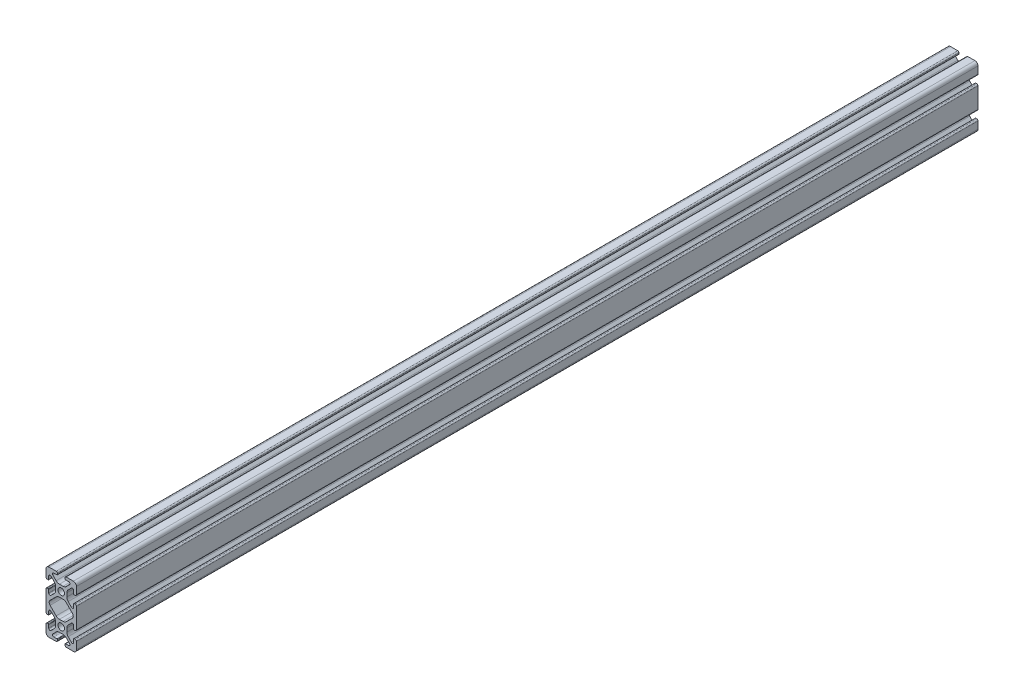
SolidWorks part; units mm, degrees
ref_plane "Front Plane" through (0, 0, 0) normal (0, 0, 1) x (1, 0, 0)
ref_plane "Top Plane" through (0, 0, 0) normal (0, 1, 0) x (1, 0, 0)
ref_plane "Right Plane" through (0, 0, 0) normal (1, 0, 0) x (0, 0, -1)
sketch "Sketch1" plane through (0, 0, 0) normal (0, 0, 1) x (1, 0, 0)
  line L0 (0, 10) -> (0, 20) construction
  line L1 (0, 10) -> (10, 10) construction
  line L2 (0, 10) -> (-10, 20) construction
  line L3 (-8, 20) -> (-3.3, 20)
  line L4 (-10, 20) -> (0, 20) construction
  line L6 (-2.8, 18.2) -> (-4.9051, 18.2)
  line L10 (0, 13.7) -> (-1.2022, 13.7)
  line L11 (-3.3236, 14.5787) -> (-5.5025, 16.7576)
  line L24 (0, 10) -> (-10, 10) construction
  line L25 (-10, 10) -> (0, 10) construction
  line L27 (-10, 0) -> (-10, 20) construction
  line L28 (0, 20) -> (10, 20) construction
  line L29 (-2.5, 18.5) -> (-2.5, 19.2)
  line L30 (-10, -20) -> (10, -20) construction
  line L31 (0, 20) -> (0, -20) construction
  arc A0 (-9.4142, 19.4142) -> (-8, 20) centre (-8, 18) cw
  arc A5 (-3.3, 20) -> (-2.5, 19.2) centre (-3.3, 19.2) cw
  arc A6 (-1.2022, 13.7) -> (-3.3236, 14.5787) centre (-1.2022, 16.7) cw
  circle A16 centre (0, 10) radius 2.15
  arc A18 (-5.5025, 16.7576) -> (-4.9051, 18.2) centre (-4.9051, 17.3551) cw
  arc A20 (-2.8, 18.2) -> (-2.5, 18.5) centre (-2.8, 18.5) ccw
  point P15 (0, -20)
  point P24 (0, 0)
  point P42 (-2.4449, 13.7)
  point P80 (-10, 10)
  dimension "D11" = 2
  dimension "D15" = 3
  dimension "Center Hole Diameter" = 4.3
  dimension "D7" = 0.8
  dimension "D8" = 0.3
  dimension "D4" = 0.8449
  dimension "D1" = 45
  dimension "Rail Width" = 20
  dimension "T-Slot Depth" = 6.3
  dimension "D9" = 1.8
  dimension "D23" = 7.4
  dimension "D5" = 11.5
  dimension "T-Slot Width" = 5
  dimension "D3" = 1.775
  dimension "D6" = 9.8102
  dimension "Rail Height" = 40
sketch "Sketch2" plane through (0, 0, 0) normal (1, 0, 0) x (0, 0, -1)
  line L0 (-304.8, 0) -> (304.8, 0)
  line L1 (-304.8, -20) -> (-304.8, 20)
  line L2 (0, 10) -> (0, 20) construction
  line L3 (0, 0) -> (0, 20) construction
  line L4 (304.8, -20) -> (304.8, 20)
  line L5 (-10, 10) -> (10, 10) construction
  point P0 (-279.8, 0)
  point P3 (0, 0)
  point P7 (279.8, 0)
  point P11 (-304.8, 0)
  point P14 (304.8, 0)
  point P23 (0, 10)
  dimension "D1" = 25
  dimension "Length" = 609.6
sketch "Sketch3" plane through (0, 0, 0) normal (0, 0, 1) x (1, 0, 0)
  line L0 (-2.5, 18.5) -> (-2.5, 19.2) construction
  line L1 (0, 10) -> (-10, 20) construction
  line L2 (0, 10) -> (-10, 20) construction
  line L5 (-8, 20) -> (-3.3, 20) construction
  line L6 (-2.8, 18.2) -> (-4.9051, 18.2) construction
  line L7 (-8.5, 7.5) -> (-9.2, 7.5)
  line L17 (-2.5, 18.5) -> (-2.5, 19.2)
  line L19 (-2.8, 18.2) -> (-4.9051, 18.2)
  line L21 (-3.7, 10) -> (0, 10) construction
  line L22 (-3.7, 8.7978) -> (-3.7, 11.2022)
  line L23 (-4.5787, 13.3236) -> (-6.7576, 15.5025)
  line L42 (-3.3236, 14.5787) -> (-5.5025, 16.7576) construction
  line L43 (0, 13.7) -> (-1.2022, 13.7) construction
  line L44 (-8, 20) -> (-3.3, 20)
  line L47 (-3.3236, 14.5787) -> (-5.5025, 16.7576)
  line L48 (1.2022, 13.7) -> (-1.2022, 13.7)
  line L59 (0, 13.7) -> (0, 12.15) construction
  line L60 (-10, 18) -> (-10, 13.3)
  line L61 (-8.2, 12.8) -> (-8.2, 14.9051)
  line L62 (-8.5, 12.5) -> (-9.2, 12.5)
  line L63 (-8.2, 7.2) -> (-8.2, 5.0949)
  line L64 (-10, 0) -> (-10, 6.7)
  line L65 (1.2022, 6.3) -> (-1.2022, 6.3)
  line L66 (-3.3236, 5.4213) -> (-7.3307, 1.4142)
  line L68 (-4.5787, 6.6764) -> (-6.7576, 4.4975)
  line L73 (10, 0) -> (-10, 0) construction
  line L78 (4.5787, 6.6764) -> (6.7576, 4.4975)
  line L79 (3.3236, 5.4213) -> (7.3307, 1.4142)
  line L81 (10, 0) -> (10, 6.7)
  line L82 (8.2, 7.2) -> (8.2, 5.0949)
  line L83 (8.5, 12.5) -> (9.2, 12.5)
  line L84 (8.2, 12.8) -> (8.2, 14.9051)
  line L85 (10, 18) -> (10, 13.3)
  line L87 (3.3236, 14.5787) -> (5.5025, 16.7576)
  line L88 (8, 20) -> (3.3, 20)
  line L89 (4.5787, 13.3236) -> (6.7576, 15.5025)
  line L90 (3.7, 8.7978) -> (3.7, 11.2022)
  line L91 (2.8, 18.2) -> (4.9051, 18.2)
  line L92 (2.5, 18.5) -> (2.5, 19.2)
  line L93 (8.5, 7.5) -> (9.2, 7.5)
  line L94 (-10, 0) -> (-7.9165, 0)
  line L96 (7.9165, 0) -> (10, 0)
  arc A0 (-8, 20) -> (-9.4142, 19.4142) centre (-8, 18) ccw construction
  arc A1 (-2.8, 18.2) -> (-2.5, 18.5) centre (-2.8, 18.5) ccw construction
  arc A3 (-2.8, 18.2) -> (-2.5, 18.5) centre (-2.8, 18.5) ccw
  arc A5 (-8, 20) -> (-10, 18) centre (-8, 18) ccw
  arc A10 (-3.3236, 5.4213) -> (-1.2022, 6.3) centre (-1.2022, 3.3) cw
  circle A13 centre (0, 10) radius 2.15 construction
  circle A14 centre (0, 10) radius 2.15
  arc A15 (-4.5787, 13.3236) -> (-3.7, 11.2022) centre (-6.7, 11.2022) cw
  arc A16 (-8.2, 14.9051) -> (-6.7576, 15.5025) centre (-7.3551, 14.9051) cw
  arc A17 (-9.2, 12.5) -> (-10, 13.3) centre (-9.2, 13.3) cw
  arc A18 (-8.2, 12.8) -> (-8.5, 12.5) centre (-8.5, 12.8) cw
  arc A36 (-2.5, 19.2) -> (-3.3, 20) centre (-3.3, 19.2) ccw construction
  arc A38 (-4.9051, 18.2) -> (-5.5025, 16.7576) centre (-4.9051, 17.3551) ccw construction
  arc A39 (-3.3236, 14.5787) -> (-1.2022, 13.7) centre (-1.2022, 16.7) ccw construction
  arc A41 (-2.5, 19.2) -> (-3.3, 20) centre (-3.3, 19.2) ccw
  arc A43 (-4.9051, 18.2) -> (-5.5025, 16.7576) centre (-4.9051, 17.3551) ccw
  arc A44 (-3.3236, 14.5787) -> (-1.2022, 13.7) centre (-1.2022, 16.7) ccw
  arc A47 (-8.2, 7.2) -> (-8.5, 7.5) centre (-8.5, 7.2) ccw
  arc A48 (-9.2, 7.5) -> (-10, 6.7) centre (-9.2, 6.7) ccw
  arc A49 (-8.2, 5.0949) -> (-6.7576, 4.4975) centre (-7.3551, 5.0949) ccw
  arc A50 (-4.5787, 6.6764) -> (-3.7, 8.7978) centre (-6.7, 8.7978) ccw
  arc A54 (-7.9165, 0) -> (-7.3307, 1.4142) centre (-5.9165, 0) cw
  arc A57 (7.9165, 0) -> (7.3307, 1.4142) centre (5.9165, 0) ccw
  arc A58 (4.5787, 6.6764) -> (3.7, 8.7978) centre (6.7, 8.7978) cw
  arc A59 (8.2, 5.0949) -> (6.7576, 4.4975) centre (7.3551, 5.0949) cw
  arc A60 (9.2, 7.5) -> (10, 6.7) centre (9.2, 6.7) cw
  arc A61 (8.2, 7.2) -> (8.5, 7.5) centre (8.5, 7.2) cw
  arc A62 (3.3236, 14.5787) -> (1.2022, 13.7) centre (1.2022, 16.7) cw
  arc A63 (4.9051, 18.2) -> (5.5025, 16.7576) centre (4.9051, 17.3551) cw
  arc A64 (2.5, 19.2) -> (3.3, 20) centre (3.3, 19.2) cw
  arc A65 (8.2, 12.8) -> (8.5, 12.5) centre (8.5, 12.8) ccw
  arc A66 (9.2, 12.5) -> (10, 13.3) centre (9.2, 13.3) ccw
  arc A67 (8.2, 14.9051) -> (6.7576, 15.5025) centre (7.3551, 14.9051) ccw
  arc A68 (4.5787, 13.3236) -> (3.7, 11.2022) centre (6.7, 11.2022) ccw
  arc A70 (3.3236, 5.4213) -> (1.2022, 6.3) centre (1.2022, 3.3) ccw
  arc A71 (8, 20) -> (10, 18) centre (8, 18) cw
  arc A72 (2.8, 18.2) -> (2.5, 18.5) centre (2.8, 18.5) cw
  point P59 (-10, 2)
  point P71 (0, 0)
  point P116 (0, 6.3)
extrude "Boss-Extrude1" add sketch "Sketch3" along normal mid plane 609.6
pattern_circular "CirPattern1" count 2 over 360 about axis through (0, 0, 0) along (0, 0, 1) of "Boss-Extrude1"
sketch "Sketch4" plane through (0, 0, 304.8) normal (0, 0, 1) x (1, 0, 0)
  line L0 (7.3307, -1.4142) -> (3.3236, -5.4213) construction
  line L1 (-3.3236, -5.4213) -> (-7.3307, -1.4142) construction
  line L2 (1.2022, -6.3) -> (-1.2022, -6.3) construction
  line L3 (3.3236, 5.4213) -> (7.3307, 1.4142) construction
  line L4 (-1.2022, 6.3) -> (1.2022, 6.3) construction
  line L5 (-7.3307, 1.4142) -> (-3.3236, 5.4213) construction
  line L6 (7.3307, -1.4142) -> (3.3236, -5.4213)
  line L7 (-3.3236, -5.4213) -> (-7.3307, -1.4142)
  line L8 (1.2022, -6.3) -> (-1.2022, -6.3)
  line L9 (3.3236, 5.4213) -> (7.3307, 1.4142)
  line L10 (-1.2022, 6.3) -> (1.2022, 6.3)
  line L11 (-7.3307, 1.4142) -> (-3.3236, 5.4213)
  line L52 (-2.5, 18.5) -> (-2.5, 19.2)
  line L53 (-3.3, 20) -> (-8, 20)
  line L54 (-10, 18) -> (-10, 13.3)
  line L55 (-9.2, 12.5) -> (-8.5, 12.5)
  line L56 (-8.2, 12.8) -> (-8.2, 14.9051)
  line L57 (-6.7576, 15.5025) -> (-4.5787, 13.3236)
  line L58 (-3.7, 11.2022) -> (-3.7, 8.7978)
  line L59 (-4.5787, 6.6764) -> (-6.7576, 4.4975)
  line L60 (-8.2, 5.0949) -> (-8.2, 7.2)
  line L61 (-8.5, 7.5) -> (-9.2, 7.5)
  line L62 (-10, 6.7) -> (-10, -6.7)
  line L63 (-9.2, -7.5) -> (-8.5, -7.5)
  line L64 (-8.2, -7.2) -> (-8.2, -5.0949)
  line L65 (-6.7576, -4.4975) -> (-4.5787, -6.6764)
  line L66 (-3.7, -8.7978) -> (-3.7, -11.2022)
  line L67 (-4.5787, -13.3236) -> (-6.7576, -15.5025)
  line L68 (-8.2, -14.9051) -> (-8.2, -12.8)
  line L69 (-8.5, -12.5) -> (-9.2, -12.5)
  line L70 (-10, -13.3) -> (-10, -18)
  line L71 (-8, -20) -> (-3.3, -20)
  line L72 (-2.5, -19.2) -> (-2.5, -18.5)
  line L73 (-2.8, -18.2) -> (-4.9051, -18.2)
  line L74 (-5.5025, -16.7576) -> (-3.3236, -14.5787)
  line L75 (-1.2022, -13.7) -> (1.2022, -13.7)
  line L76 (3.3236, -14.5787) -> (5.5025, -16.7576)
  line L77 (4.9051, -18.2) -> (2.8, -18.2)
  line L78 (2.5, -18.5) -> (2.5, -19.2)
  line L79 (3.3, -20) -> (8, -20)
  line L80 (10, -18) -> (10, -13.3)
  line L81 (9.2, -12.5) -> (8.5, -12.5)
  line L82 (8.2, -12.8) -> (8.2, -14.9051)
  line L83 (6.7576, -15.5025) -> (4.5787, -13.3236)
  line L84 (3.7, -11.2022) -> (3.7, -8.7978)
  line L85 (4.5787, -6.6764) -> (6.7576, -4.4975)
  line L86 (8.2, -5.0949) -> (8.2, -7.2)
  line L87 (8.5, -7.5) -> (9.2, -7.5)
  line L88 (10, -6.7) -> (10, 6.7)
  line L89 (9.2, 7.5) -> (8.5, 7.5)
  line L90 (8.2, 7.2) -> (8.2, 5.0949)
  line L91 (6.7576, 4.4975) -> (4.5787, 6.6764)
  line L92 (3.7, 8.7978) -> (3.7, 11.2022)
  line L93 (4.5787, 13.3236) -> (6.7576, 15.5025)
  line L94 (8.2, 14.9051) -> (8.2, 12.8)
  line L95 (8.5, 12.5) -> (9.2, 12.5)
  line L96 (10, 13.3) -> (10, 18)
  line L97 (8, 20) -> (3.3, 20)
  line L98 (2.5, 19.2) -> (2.5, 18.5)
  line L99 (2.8, 18.2) -> (4.9051, 18.2)
  line L100 (5.5025, 16.7576) -> (3.3236, 14.5787)
  line L101 (1.2022, 13.7) -> (-1.2022, 13.7)
  line L102 (-3.3236, 14.5787) -> (-5.5025, 16.7576)
  line L103 (-4.9051, 18.2) -> (-2.8, 18.2)
  line L104 (-2.5, 18.5) -> (-2.5, 19.2)
  line L105 (-3.3, 20) -> (-8, 20)
  line L106 (-10, 18) -> (-10, 13.3)
  line L107 (-9.2, 12.5) -> (-8.5, 12.5)
  line L108 (-8.2, 12.8) -> (-8.2, 14.9051)
  line L109 (-6.7576, 15.5025) -> (-4.5787, 13.3236)
  line L110 (-3.7, 11.2022) -> (-3.7, 8.7978)
  line L111 (-4.5787, 6.6764) -> (-6.7576, 4.4975)
  line L112 (-8.2, 5.0949) -> (-8.2, 7.2)
  line L113 (-8.5, 7.5) -> (-9.2, 7.5)
  line L114 (-10, 6.7) -> (-10, -6.7)
  line L115 (-9.2, -7.5) -> (-8.5, -7.5)
  line L116 (-8.2, -7.2) -> (-8.2, -5.0949)
  line L117 (-6.7576, -4.4975) -> (-4.5787, -6.6764)
  line L118 (-3.7, -8.7978) -> (-3.7, -11.2022)
  line L119 (-4.5787, -13.3236) -> (-6.7576, -15.5025)
  line L120 (-8.2, -14.9051) -> (-8.2, -12.8)
  line L121 (-8.5, -12.5) -> (-9.2, -12.5)
  line L122 (-10, -13.3) -> (-10, -18)
  line L123 (-8, -20) -> (-3.3, -20)
  line L124 (-2.5, -19.2) -> (-2.5, -18.5)
  line L125 (-2.8, -18.2) -> (-4.9051, -18.2)
  line L126 (-5.5025, -16.7576) -> (-3.3236, -14.5787)
  line L127 (-1.2022, -13.7) -> (1.2022, -13.7)
  line L128 (3.3236, -14.5787) -> (5.5025, -16.7576)
  line L129 (4.9051, -18.2) -> (2.8, -18.2)
  line L130 (2.5, -18.5) -> (2.5, -19.2)
  line L131 (3.3, -20) -> (8, -20)
  line L132 (10, -18) -> (10, -13.3)
  line L133 (9.2, -12.5) -> (8.5, -12.5)
  line L134 (8.2, -12.8) -> (8.2, -14.9051)
  line L135 (6.7576, -15.5025) -> (4.5787, -13.3236)
  line L136 (3.7, -11.2022) -> (3.7, -8.7978)
  line L137 (4.5787, -6.6764) -> (6.7576, -4.4975)
  line L138 (8.2, -5.0949) -> (8.2, -7.2)
  line L139 (8.5, -7.5) -> (9.2, -7.5)
  line L140 (10, -6.7) -> (10, 6.7)
  line L141 (9.2, 7.5) -> (8.5, 7.5)
  line L142 (8.2, 7.2) -> (8.2, 5.0949)
  line L143 (6.7576, 4.4975) -> (4.5787, 6.6764)
  line L144 (3.7, 8.7978) -> (3.7, 11.2022)
  line L145 (4.5787, 13.3236) -> (6.7576, 15.5025)
  line L146 (8.2, 14.9051) -> (8.2, 12.8)
  line L147 (8.5, 12.5) -> (9.2, 12.5)
  line L148 (10, 13.3) -> (10, 18)
  line L149 (8, 20) -> (3.3, 20)
  line L150 (2.5, 19.2) -> (2.5, 18.5)
  line L151 (2.8, 18.2) -> (4.9051, 18.2)
  line L152 (5.5025, 16.7576) -> (3.3236, 14.5787)
  line L153 (1.2022, 13.7) -> (-1.2022, 13.7)
  line L154 (-3.3236, 14.5787) -> (-5.5025, 16.7576)
  line L155 (-4.9051, 18.2) -> (-2.8, 18.2)
  circle A0 centre (0, 10) radius 2.15 construction
  arc A1 (-7.3307, 1.4142) -> (-7.3307, -1.4142) centre (-5.9165, 0) ccw construction
  arc A2 (-3.3236, -5.4213) -> (-1.2022, -6.3) centre (-1.2022, -3.3) ccw construction
  arc A3 (1.2022, -6.3) -> (3.3236, -5.4213) centre (1.2022, -3.3) ccw construction
  circle A4 centre (0, -10) radius 2.15 construction
  arc A5 (7.3307, -1.4142) -> (7.3307, 1.4142) centre (5.9165, 0) ccw construction
  arc A6 (3.3236, 5.4213) -> (1.2022, 6.3) centre (1.2022, 3.3) ccw construction
  arc A7 (-1.2022, 6.3) -> (-3.3236, 5.4213) centre (-1.2022, 3.3) ccw construction
  circle A8 centre (0, 10) radius 2.15
  arc A9 (-7.3307, 1.4142) -> (-7.3307, -1.4142) centre (-5.9165, 0) ccw
  arc A10 (-3.3236, -5.4213) -> (-1.2022, -6.3) centre (-1.2022, -3.3) ccw
  arc A11 (1.2022, -6.3) -> (3.3236, -5.4213) centre (1.2022, -3.3) ccw
  circle A12 centre (0, -10) radius 2.15
  arc A13 (7.3307, -1.4142) -> (7.3307, 1.4142) centre (5.9165, 0) ccw
  arc A14 (3.3236, 5.4213) -> (1.2022, 6.3) centre (1.2022, 3.3) ccw
  arc A15 (-1.2022, 6.3) -> (-3.3236, 5.4213) centre (-1.2022, 3.3) ccw
  arc A52 (-2.8, 18.2) -> (-2.5, 18.5) centre (-2.8, 18.5) ccw
  arc A53 (-2.5, 19.2) -> (-3.3, 20) centre (-3.3, 19.2) ccw
  arc A54 (-8, 20) -> (-10, 18) centre (-8, 18) ccw
  arc A55 (-10, 13.3) -> (-9.2, 12.5) centre (-9.2, 13.3) ccw
  arc A56 (-8.5, 12.5) -> (-8.2, 12.8) centre (-8.5, 12.8) ccw
  arc A57 (-6.7576, 15.5025) -> (-8.2, 14.9051) centre (-7.3551, 14.9051) ccw
  arc A58 (-3.7, 11.2022) -> (-4.5787, 13.3236) centre (-6.7, 11.2022) ccw
  arc A59 (-4.5787, 6.6764) -> (-3.7, 8.7978) centre (-6.7, 8.7978) ccw
  arc A60 (-8.2, 5.0949) -> (-6.7576, 4.4975) centre (-7.3551, 5.0949) ccw
  arc A61 (-8.2, 7.2) -> (-8.5, 7.5) centre (-8.5, 7.2) ccw
  arc A62 (-9.2, 7.5) -> (-10, 6.7) centre (-9.2, 6.7) ccw
  arc A63 (-10, -6.7) -> (-9.2, -7.5) centre (-9.2, -6.7) ccw
  arc A64 (-8.5, -7.5) -> (-8.2, -7.2) centre (-8.5, -7.2) ccw
  arc A65 (-6.7576, -4.4975) -> (-8.2, -5.0949) centre (-7.3551, -5.0949) ccw
  arc A66 (-3.7, -8.7978) -> (-4.5787, -6.6764) centre (-6.7, -8.7978) ccw
  arc A67 (-4.5787, -13.3236) -> (-3.7, -11.2022) centre (-6.7, -11.2022) ccw
  arc A68 (-8.2, -14.9051) -> (-6.7576, -15.5025) centre (-7.3551, -14.9051) ccw
  arc A69 (-8.2, -12.8) -> (-8.5, -12.5) centre (-8.5, -12.8) ccw
  arc A70 (-9.2, -12.5) -> (-10, -13.3) centre (-9.2, -13.3) ccw
  arc A71 (-10, -18) -> (-8, -20) centre (-8, -18) ccw
  arc A72 (-3.3, -20) -> (-2.5, -19.2) centre (-3.3, -19.2) ccw
  arc A73 (-2.5, -18.5) -> (-2.8, -18.2) centre (-2.8, -18.5) ccw
  arc A74 (-5.5025, -16.7576) -> (-4.9051, -18.2) centre (-4.9051, -17.3551) ccw
  arc A75 (-1.2022, -13.7) -> (-3.3236, -14.5787) centre (-1.2022, -16.7) ccw
  arc A76 (3.3236, -14.5787) -> (1.2022, -13.7) centre (1.2022, -16.7) ccw
  arc A77 (4.9051, -18.2) -> (5.5025, -16.7576) centre (4.9051, -17.3551) ccw
  arc A78 (2.8, -18.2) -> (2.5, -18.5) centre (2.8, -18.5) ccw
  arc A79 (2.5, -19.2) -> (3.3, -20) centre (3.3, -19.2) ccw
  arc A80 (8, -20) -> (10, -18) centre (8, -18) ccw
  arc A81 (10, -13.3) -> (9.2, -12.5) centre (9.2, -13.3) ccw
  arc A82 (8.5, -12.5) -> (8.2, -12.8) centre (8.5, -12.8) ccw
  arc A83 (6.7576, -15.5025) -> (8.2, -14.9051) centre (7.3551, -14.9051) ccw
  arc A84 (3.7, -11.2022) -> (4.5787, -13.3236) centre (6.7, -11.2022) ccw
  arc A85 (4.5787, -6.6764) -> (3.7, -8.7978) centre (6.7, -8.7978) ccw
  arc A86 (8.2, -5.0949) -> (6.7576, -4.4975) centre (7.3551, -5.0949) ccw
  arc A87 (8.2, -7.2) -> (8.5, -7.5) centre (8.5, -7.2) ccw
  arc A88 (9.2, -7.5) -> (10, -6.7) centre (9.2, -6.7) ccw
  arc A89 (10, 6.7) -> (9.2, 7.5) centre (9.2, 6.7) ccw
  arc A90 (8.5, 7.5) -> (8.2, 7.2) centre (8.5, 7.2) ccw
  arc A91 (6.7576, 4.4975) -> (8.2, 5.0949) centre (7.3551, 5.0949) ccw
  arc A92 (3.7, 8.7978) -> (4.5787, 6.6764) centre (6.7, 8.7978) ccw
  arc A93 (4.5787, 13.3236) -> (3.7, 11.2022) centre (6.7, 11.2022) ccw
  arc A94 (8.2, 14.9051) -> (6.7576, 15.5025) centre (7.3551, 14.9051) ccw
  arc A95 (8.2, 12.8) -> (8.5, 12.5) centre (8.5, 12.8) ccw
  arc A96 (9.2, 12.5) -> (10, 13.3) centre (9.2, 13.3) ccw
  arc A97 (10, 18) -> (8, 20) centre (8, 18) ccw
  arc A98 (3.3, 20) -> (2.5, 19.2) centre (3.3, 19.2) ccw
  arc A99 (2.5, 18.5) -> (2.8, 18.2) centre (2.8, 18.5) ccw
  arc A100 (5.5025, 16.7576) -> (4.9051, 18.2) centre (4.9051, 17.3551) ccw
  arc A101 (1.2022, 13.7) -> (3.3236, 14.5787) centre (1.2022, 16.7) ccw
  arc A102 (-3.3236, 14.5787) -> (-1.2022, 13.7) centre (-1.2022, 16.7) ccw
  arc A103 (-4.9051, 18.2) -> (-5.5025, 16.7576) centre (-4.9051, 17.3551) ccw
  arc A104 (-2.8, 18.2) -> (-2.5, 18.5) centre (-2.8, 18.5) ccw
  arc A105 (-2.5, 19.2) -> (-3.3, 20) centre (-3.3, 19.2) ccw
  arc A106 (-8, 20) -> (-10, 18) centre (-8, 18) ccw
  arc A107 (-10, 13.3) -> (-9.2, 12.5) centre (-9.2, 13.3) ccw
  arc A108 (-8.5, 12.5) -> (-8.2, 12.8) centre (-8.5, 12.8) ccw
  arc A109 (-6.7576, 15.5025) -> (-8.2, 14.9051) centre (-7.3551, 14.9051) ccw
  arc A110 (-3.7, 11.2022) -> (-4.5787, 13.3236) centre (-6.7, 11.2022) ccw
  arc A111 (-4.5787, 6.6764) -> (-3.7, 8.7978) centre (-6.7, 8.7978) ccw
  arc A112 (-8.2, 5.0949) -> (-6.7576, 4.4975) centre (-7.3551, 5.0949) ccw
  arc A113 (-8.2, 7.2) -> (-8.5, 7.5) centre (-8.5, 7.2) ccw
  arc A114 (-9.2, 7.5) -> (-10, 6.7) centre (-9.2, 6.7) ccw
  arc A115 (-10, -6.7) -> (-9.2, -7.5) centre (-9.2, -6.7) ccw
  arc A116 (-8.5, -7.5) -> (-8.2, -7.2) centre (-8.5, -7.2) ccw
  arc A117 (-6.7576, -4.4975) -> (-8.2, -5.0949) centre (-7.3551, -5.0949) ccw
  arc A118 (-3.7, -8.7978) -> (-4.5787, -6.6764) centre (-6.7, -8.7978) ccw
  arc A119 (-4.5787, -13.3236) -> (-3.7, -11.2022) centre (-6.7, -11.2022) ccw
  arc A120 (-8.2, -14.9051) -> (-6.7576, -15.5025) centre (-7.3551, -14.9051) ccw
  arc A121 (-8.2, -12.8) -> (-8.5, -12.5) centre (-8.5, -12.8) ccw
  arc A122 (-9.2, -12.5) -> (-10, -13.3) centre (-9.2, -13.3) ccw
  arc A123 (-10, -18) -> (-8, -20) centre (-8, -18) ccw
  arc A124 (-3.3, -20) -> (-2.5, -19.2) centre (-3.3, -19.2) ccw
  arc A125 (-2.5, -18.5) -> (-2.8, -18.2) centre (-2.8, -18.5) ccw
  arc A126 (-5.5025, -16.7576) -> (-4.9051, -18.2) centre (-4.9051, -17.3551) ccw
  arc A127 (-1.2022, -13.7) -> (-3.3236, -14.5787) centre (-1.2022, -16.7) ccw
  arc A128 (3.3236, -14.5787) -> (1.2022, -13.7) centre (1.2022, -16.7) ccw
  arc A129 (4.9051, -18.2) -> (5.5025, -16.7576) centre (4.9051, -17.3551) ccw
  arc A130 (2.8, -18.2) -> (2.5, -18.5) centre (2.8, -18.5) ccw
  arc A131 (2.5, -19.2) -> (3.3, -20) centre (3.3, -19.2) ccw
  arc A132 (8, -20) -> (10, -18) centre (8, -18) ccw
  arc A133 (10, -13.3) -> (9.2, -12.5) centre (9.2, -13.3) ccw
  arc A134 (8.5, -12.5) -> (8.2, -12.8) centre (8.5, -12.8) ccw
  arc A135 (6.7576, -15.5025) -> (8.2, -14.9051) centre (7.3551, -14.9051) ccw
  arc A136 (3.7, -11.2022) -> (4.5787, -13.3236) centre (6.7, -11.2022) ccw
  arc A137 (4.5787, -6.6764) -> (3.7, -8.7978) centre (6.7, -8.7978) ccw
  arc A138 (8.2, -5.0949) -> (6.7576, -4.4975) centre (7.3551, -5.0949) ccw
  arc A139 (8.2, -7.2) -> (8.5, -7.5) centre (8.5, -7.2) ccw
  arc A140 (9.2, -7.5) -> (10, -6.7) centre (9.2, -6.7) ccw
  arc A141 (10, 6.7) -> (9.2, 7.5) centre (9.2, 6.7) ccw
  arc A142 (8.5, 7.5) -> (8.2, 7.2) centre (8.5, 7.2) ccw
  arc A143 (6.7576, 4.4975) -> (8.2, 5.0949) centre (7.3551, 5.0949) ccw
  arc A144 (3.7, 8.7978) -> (4.5787, 6.6764) centre (6.7, 8.7978) ccw
  arc A145 (4.5787, 13.3236) -> (3.7, 11.2022) centre (6.7, 11.2022) ccw
  arc A146 (8.2, 14.9051) -> (6.7576, 15.5025) centre (7.3551, 14.9051) ccw
  arc A147 (8.2, 12.8) -> (8.5, 12.5) centre (8.5, 12.8) ccw
  arc A148 (9.2, 12.5) -> (10, 13.3) centre (9.2, 13.3) ccw
  arc A149 (10, 18) -> (8, 20) centre (8, 18) ccw
  arc A150 (3.3, 20) -> (2.5, 19.2) centre (3.3, 19.2) ccw
  arc A151 (2.5, 18.5) -> (2.8, 18.2) centre (2.8, 18.5) ccw
  arc A152 (5.5025, 16.7576) -> (4.9051, 18.2) centre (4.9051, 17.3551) ccw
  arc A153 (1.2022, 13.7) -> (3.3236, 14.5787) centre (1.2022, 16.7) ccw
  arc A154 (-3.3236, 14.5787) -> (-1.2022, 13.7) centre (-1.2022, 16.7) ccw
  arc A155 (-4.9051, 18.2) -> (-5.5025, 16.7576) centre (-4.9051, 17.3551) ccw
  dimension "D1" = 0
extrude "Cut-Extrude1" cut sketch "Sketch4" against normal blind 17.07
equation "\"D1@Sketch2\"=\"Rail Width@Sketch1\"*1.25"
equation "\"D1@Boss-Extrude1\" = \"Length@Sketch2\""
